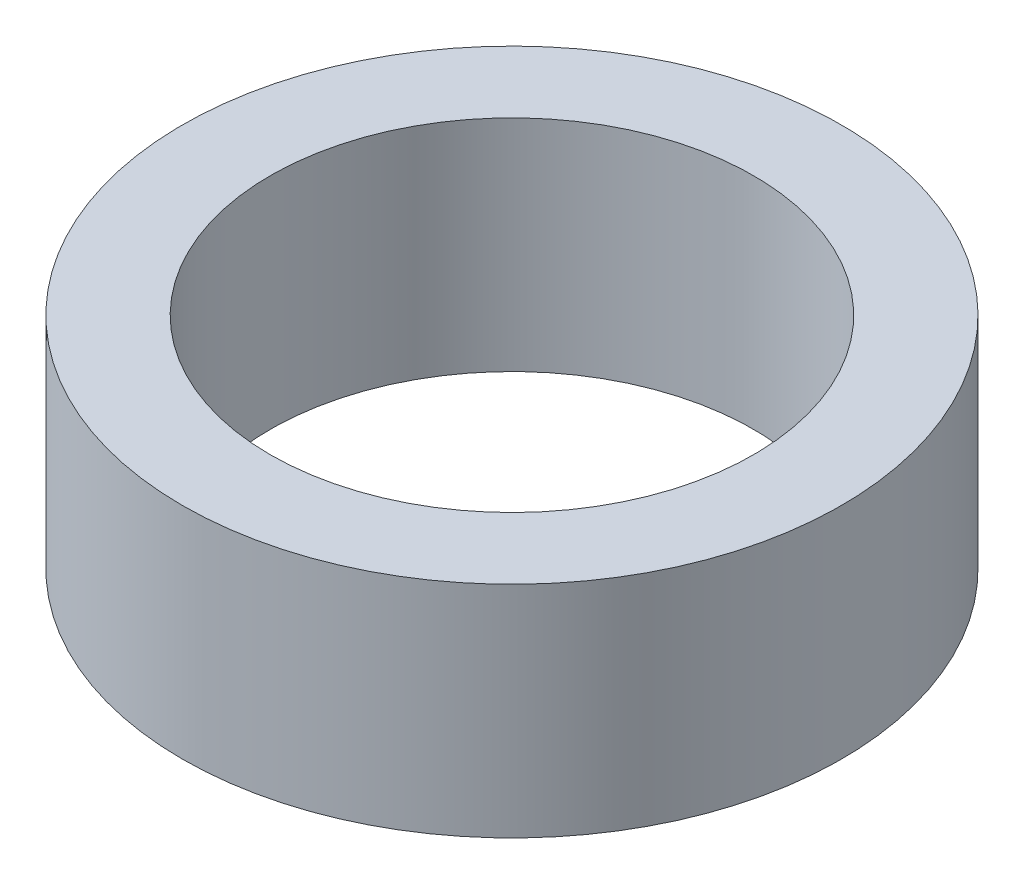
SolidWorks part; units mm, degrees
ref_plane "前视基准面" through (0, 0, 0) normal (0, 0, 1) x (1, 0, 0)
ref_plane "上视基准面" through (0, 0, 0) normal (0, 1, 0) x (1, 0, 0)
ref_plane "右视基准面" through (0, 0, 0) normal (1, 0, 0) x (0, 0, -1)
sketch "草图1" plane through (0, 0, 0) normal (0, 1, 0) x (1, 0, 0)
  circle A0 centre (0, 0) radius 2.75
  circle A1 centre (0, 0) radius 3.75
  dimension "D1" = 5.5
  dimension "D2" = 7.5
extrude "凸台-拉伸1" add sketch "草图1" along normal blind 2.5
